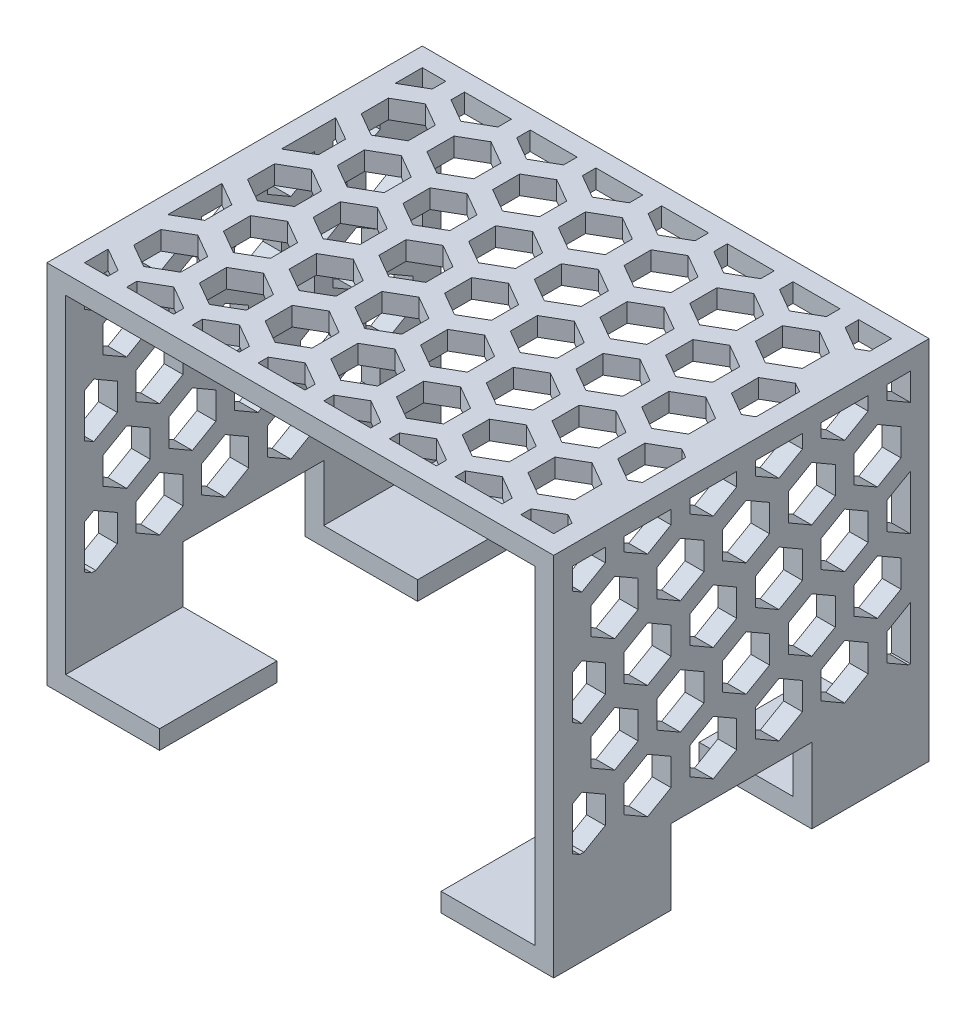
SolidWorks part; units mm, degrees
ref_plane "前视基准面" through (0, 0, 0) normal (0, 0, 1) x (1, 0, 0)
ref_plane "上视基准面" through (0, 0, 0) normal (0, 1, 0) x (1, 0, 0)
ref_plane "右视基准面" through (0, 0, 0) normal (1, 0, 0) x (0, 0, -1)
sketch "草图1" plane through (0, 0, 0) normal (0, 0, 1) x (1, 0, 0)
  line L0 (-13.2124, -10.506) -> (-23.2124, -10.506)
  line L1 (-23.2124, 24.494) -> (26.7876, 24.494)
  line L2 (-23.2124, 24.494) -> (-23.2124, -10.506)
  line L3 (-23.2124, -12.506) -> (-13.2124, -12.506)
  line L4 (26.7876, 24.494) -> (26.7876, -10.506)
  line L6 (-13.2124, -12.506) -> (-13.2124, -10.506)
  line L8 (16.7876, -12.506) -> (16.7876, -10.506)
  line L10 (-23.2124, 24.494) -> (-23.2124, -10.506)
  line L11 (-23.2124, -12.506) -> (-25.2124, -12.506)
  line L12 (-25.2124, 22.494) -> (-25.2124, -12.506)
  line L14 (26.7876, 24.494) -> (26.7876, -10.506)
  line L15 (26.7876, -12.506) -> (28.7876, -12.506)
  line L16 (28.7876, 23.4681) -> (28.7876, -12.506)
  line L17 (-23.2124, 24.494) -> (26.7876, 24.494)
  line L18 (-25.2124, 22.494) -> (-25.2124, 26.494)
  line L19 (-25.2124, 26.494) -> (28.7876, 26.494)
  line L20 (28.7876, 23.4681) -> (28.7876, 26.494)
  line L21 (16.7876, -10.506) -> (26.7876, -10.506)
  line L22 (16.7876, -12.506) -> (26.7876, -12.506)
  dimension "D1" = 50
  dimension "D2" = 37
  dimension "D3" = 30
  dimension "D4" = 10
  dimension "D5" = 2
  dimension "D6" = 2
  dimension "D7" = 2
  dimension "D9" = 2
extrude "凸台-拉伸1" add sketch "草图1" along normal blind 40 contours L8 L22 L15 L16 L20 L19 L18 L12 L11 L3 L6 L0 L2 L1 L4 L21
sketch "草图2" plane through (0, 26.494, 0) normal (0, 1, 0) x (1, 0, 0)
  line L0 (-19.7124, -10.9489) -> (-17.2124, -9.5056)
  line L1 (-23.2124, -4.8868) -> (-20.7124, -3.4434)
  line L2 (-20.7124, -3.4434) -> (-20.7124, -2)
  line L7 (-17.2124, -9.5056) -> (-17.2124, -6.6188)
  line L8 (-17.2124, -6.6188) -> (-19.7124, -5.1754)
  line L9 (-19.7124, -5.1754) -> (-22.2124, -6.6188)
  line L10 (-22.2124, -6.6188) -> (-22.2124, -9.5056)
  line L11 (-22.2124, -9.5056) -> (-19.7124, -10.9489)
  line L12 (-25.2124, 0) -> (28.7876, 0) construction
  line L13 (-16.2124, -4.8868) -> (-13.7124, -3.4434)
  line L14 (-25.2124, -40) -> (-25.2124, 0) construction
  line L15 (-13.7124, -3.4434) -> (-13.7124, -2)
  line L18 (-18.7124, -2) -> (-18.7124, -3.4434)
  line L19 (-18.7124, -3.4434) -> (-16.2124, -4.8868)
  line L20 (-12.7124, -10.9489) -> (-10.2124, -9.5056)
  line L21 (-10.2124, -9.5056) -> (-10.2124, -6.6188)
  line L22 (-10.2124, -6.6188) -> (-12.7124, -5.1754)
  line L23 (-12.7124, -5.1754) -> (-15.2124, -6.6188)
  line L24 (-15.2124, -6.6188) -> (-15.2124, -9.5056)
  line L25 (-15.2124, -9.5056) -> (-12.7124, -10.9489)
  line L26 (-9.2124, -4.8868) -> (-6.7124, -3.4434)
  line L27 (-6.7124, -3.4434) -> (-6.7124, -2)
  line L30 (-11.7124, -2) -> (-11.7124, -3.4434)
  line L31 (-11.7124, -3.4434) -> (-9.2124, -4.8868)
  line L32 (-5.7124, -10.9489) -> (-3.2124, -9.5056)
  line L33 (-3.2124, -9.5056) -> (-3.2124, -6.6188)
  line L34 (-3.2124, -6.6188) -> (-5.7124, -5.1754)
  line L35 (-5.7124, -5.1754) -> (-8.2124, -6.6188)
  line L36 (-8.2124, -6.6188) -> (-8.2124, -9.5056)
  line L37 (-8.2124, -9.5056) -> (-5.7124, -10.9489)
  line L38 (-2.2124, -4.8868) -> (0.2876, -3.4434)
  line L39 (0.2876, -3.4434) -> (0.2876, -2)
  line L42 (-4.7124, -2) -> (-4.7124, -3.4434)
  line L43 (-4.7124, -3.4434) -> (-2.2124, -4.8868)
  line L44 (1.2876, -10.9489) -> (3.7876, -9.5056)
  line L45 (3.7876, -9.5056) -> (3.7876, -6.6188)
  line L46 (3.7876, -6.6188) -> (1.2876, -5.1754)
  line L47 (1.2876, -5.1754) -> (-1.2124, -6.6188)
  line L48 (-1.2124, -6.6188) -> (-1.2124, -9.5056)
  line L49 (-1.2124, -9.5056) -> (1.2876, -10.9489)
  line L50 (4.7876, -4.8868) -> (7.2876, -3.4434)
  line L51 (7.2876, -3.4434) -> (7.2876, -2)
  line L54 (2.2876, -2) -> (2.2876, -3.4434)
  line L55 (2.2876, -3.4434) -> (4.7876, -4.8868)
  line L56 (8.2876, -10.9489) -> (10.7876, -9.5056)
  line L57 (10.7876, -9.5056) -> (10.7876, -6.6188)
  line L58 (10.7876, -6.6188) -> (8.2876, -5.1754)
  line L59 (8.2876, -5.1754) -> (5.7876, -6.6188)
  line L60 (5.7876, -6.6188) -> (5.7876, -9.5056)
  line L61 (5.7876, -9.5056) -> (8.2876, -10.9489)
  line L62 (11.7876, -4.8868) -> (14.2876, -3.4434)
  line L63 (14.2876, -3.4434) -> (14.2876, -2)
  line L66 (9.2876, -2) -> (9.2876, -3.4434)
  line L67 (9.2876, -3.4434) -> (11.7876, -4.8868)
  line L68 (15.2876, -10.9489) -> (17.7876, -9.5056)
  line L69 (17.7876, -9.5056) -> (17.7876, -6.6188)
  line L70 (17.7876, -6.6188) -> (15.2876, -5.1754)
  line L71 (15.2876, -5.1754) -> (12.7876, -6.6188)
  line L72 (12.7876, -6.6188) -> (12.7876, -9.5056)
  line L73 (12.7876, -9.5056) -> (15.2876, -10.9489)
  line L74 (18.7876, -4.8868) -> (21.2876, -3.4434)
  line L75 (21.2876, -3.4434) -> (21.2876, -2)
  line L78 (16.2876, -2) -> (16.2876, -3.4434)
  line L79 (16.2876, -3.4434) -> (18.7876, -4.8868)
  line L80 (22.2876, -10.9489) -> (24.7876, -9.5056)
  line L81 (24.7876, -9.5056) -> (24.7876, -6.6188)
  line L82 (24.7876, -6.6188) -> (22.2876, -5.1754)
  line L83 (22.2876, -5.1754) -> (19.7876, -6.6188)
  line L84 (19.7876, -6.6188) -> (19.7876, -9.5056)
  line L85 (19.7876, -9.5056) -> (22.2876, -10.9489)
  line L86 (25.7876, -4.8868) -> (26.7876, -4.3094)
  line L90 (23.2876, -2) -> (23.2876, -3.4434)
  line L91 (23.2876, -3.4434) -> (25.7876, -4.8868)
  line L98 (-16.2124, -17.0068) -> (-13.7124, -15.5634)
  line L99 (-13.7124, -15.5634) -> (-13.7124, -12.6766)
  line L100 (-13.7124, -12.6766) -> (-16.2124, -11.2332)
  line L101 (-16.2124, -11.2332) -> (-18.7124, -12.6766)
  line L102 (-18.7124, -12.6766) -> (-18.7124, -15.5634)
  line L103 (-18.7124, -15.5634) -> (-16.2124, -17.0068)
  line L104 (-12.7124, -23.0689) -> (-10.2124, -21.6256)
  line L105 (-10.2124, -21.6256) -> (-10.2124, -18.7388)
  line L106 (-10.2124, -18.7388) -> (-12.7124, -17.2954)
  line L107 (-12.7124, -17.2954) -> (-15.2124, -18.7388)
  line L108 (-15.2124, -18.7388) -> (-15.2124, -21.6256)
  line L109 (-15.2124, -21.6256) -> (-12.7124, -23.0689)
  line L110 (-9.2124, -17.0068) -> (-6.7124, -15.5634)
  line L111 (-6.7124, -15.5634) -> (-6.7124, -12.6766)
  line L112 (-6.7124, -12.6766) -> (-9.2124, -11.2332)
  line L113 (-9.2124, -11.2332) -> (-11.7124, -12.6766)
  line L114 (-11.7124, -12.6766) -> (-11.7124, -15.5634)
  line L115 (-11.7124, -15.5634) -> (-9.2124, -17.0068)
  line L116 (-5.7124, -23.0689) -> (-3.2124, -21.6256)
  line L117 (-3.2124, -21.6256) -> (-3.2124, -18.7388)
  line L118 (-3.2124, -18.7388) -> (-5.7124, -17.2954)
  line L119 (-5.7124, -17.2954) -> (-8.2124, -18.7388)
  line L120 (-8.2124, -18.7388) -> (-8.2124, -21.6256)
  line L121 (-8.2124, -21.6256) -> (-5.7124, -23.0689)
  line L122 (-2.2124, -17.0068) -> (0.2876, -15.5634)
  line L123 (0.2876, -15.5634) -> (0.2876, -12.6766)
  line L124 (0.2876, -12.6766) -> (-2.2124, -11.2332)
  line L125 (-2.2124, -11.2332) -> (-4.7124, -12.6766)
  line L126 (-4.7124, -12.6766) -> (-4.7124, -15.5634)
  line L127 (-4.7124, -15.5634) -> (-2.2124, -17.0068)
  line L128 (1.2876, -23.0689) -> (3.7876, -21.6256)
  line L129 (3.7876, -21.6256) -> (3.7876, -18.7388)
  line L130 (3.7876, -18.7388) -> (1.2876, -17.2954)
  line L131 (1.2876, -17.2954) -> (-1.2124, -18.7388)
  line L132 (-1.2124, -18.7388) -> (-1.2124, -21.6256)
  line L133 (-1.2124, -21.6256) -> (1.2876, -23.0689)
  line L134 (4.7876, -17.0068) -> (7.2876, -15.5634)
  line L135 (7.2876, -15.5634) -> (7.2876, -12.6766)
  line L136 (7.2876, -12.6766) -> (4.7876, -11.2332)
  line L137 (4.7876, -11.2332) -> (2.2876, -12.6766)
  line L138 (2.2876, -12.6766) -> (2.2876, -15.5634)
  line L139 (2.2876, -15.5634) -> (4.7876, -17.0068)
  line L140 (8.2876, -23.0689) -> (10.7876, -21.6256)
  line L141 (10.7876, -21.6256) -> (10.7876, -18.7388)
  line L142 (10.7876, -18.7388) -> (8.2876, -17.2954)
  line L143 (8.2876, -17.2954) -> (5.7876, -18.7388)
  line L144 (5.7876, -18.7388) -> (5.7876, -21.6256)
  line L145 (5.7876, -21.6256) -> (8.2876, -23.0689)
  line L146 (11.7876, -17.0068) -> (14.2876, -15.5634)
  line L147 (14.2876, -15.5634) -> (14.2876, -12.6766)
  line L148 (14.2876, -12.6766) -> (11.7876, -11.2332)
  line L149 (11.7876, -11.2332) -> (9.2876, -12.6766)
  line L150 (9.2876, -12.6766) -> (9.2876, -15.5634)
  line L151 (9.2876, -15.5634) -> (11.7876, -17.0068)
  line L152 (15.2876, -23.0689) -> (17.7876, -21.6256)
  line L153 (17.7876, -21.6256) -> (17.7876, -18.7388)
  line L154 (17.7876, -18.7388) -> (15.2876, -17.2954)
  line L155 (15.2876, -17.2954) -> (12.7876, -18.7388)
  line L156 (12.7876, -18.7388) -> (12.7876, -21.6256)
  line L157 (12.7876, -21.6256) -> (15.2876, -23.0689)
  line L158 (18.7876, -17.0068) -> (21.2876, -15.5634)
  line L159 (21.2876, -15.5634) -> (21.2876, -12.6766)
  line L160 (21.2876, -12.6766) -> (18.7876, -11.2332)
  line L161 (18.7876, -11.2332) -> (16.2876, -12.6766)
  line L162 (16.2876, -12.6766) -> (16.2876, -15.5634)
  line L163 (16.2876, -15.5634) -> (18.7876, -17.0068)
  line L164 (22.2876, -23.0689) -> (24.7876, -21.6256)
  line L165 (24.7876, -21.6256) -> (24.7876, -18.7388)
  line L166 (24.7876, -18.7388) -> (22.2876, -17.2954)
  line L167 (22.2876, -17.2954) -> (19.7876, -18.7388)
  line L168 (19.7876, -18.7388) -> (19.7876, -21.6256)
  line L169 (19.7876, -21.6256) -> (22.2876, -23.0689)
  line L170 (25.7876, -17.0068) -> (26.7876, -16.4294)
  line L172 (26.7876, -11.8106) -> (25.7876, -11.2332)
  line L173 (25.7876, -11.2332) -> (23.2876, -12.6766)
  line L174 (23.2876, -12.6766) -> (23.2876, -15.5634)
  line L175 (23.2876, -15.5634) -> (25.7876, -17.0068)
  line L182 (-16.2124, -29.1268) -> (-13.7124, -27.6834)
  line L183 (-13.7124, -27.6834) -> (-13.7124, -24.7966)
  line L184 (-13.7124, -24.7966) -> (-16.2124, -23.3532)
  line L185 (-16.2124, -23.3532) -> (-18.7124, -24.7966)
  line L186 (-18.7124, -24.7966) -> (-18.7124, -27.6834)
  line L187 (-18.7124, -27.6834) -> (-16.2124, -29.1268)
  line L188 (-12.7124, -35.1889) -> (-10.2124, -33.7456)
  line L189 (-10.2124, -33.7456) -> (-10.2124, -30.8588)
  line L190 (-10.2124, -30.8588) -> (-12.7124, -29.4154)
  line L191 (-12.7124, -29.4154) -> (-15.2124, -30.8588)
  line L192 (-15.2124, -30.8588) -> (-15.2124, -33.7456)
  line L193 (-15.2124, -33.7456) -> (-12.7124, -35.1889)
  line L194 (-9.2124, -29.1268) -> (-6.7124, -27.6834)
  line L195 (-6.7124, -27.6834) -> (-6.7124, -24.7966)
  line L196 (-6.7124, -24.7966) -> (-9.2124, -23.3532)
  line L197 (-9.2124, -23.3532) -> (-11.7124, -24.7966)
  line L198 (-11.7124, -24.7966) -> (-11.7124, -27.6834)
  line L199 (-11.7124, -27.6834) -> (-9.2124, -29.1268)
  line L200 (-5.7124, -35.1889) -> (-3.2124, -33.7456)
  line L201 (-3.2124, -33.7456) -> (-3.2124, -30.8588)
  line L202 (-3.2124, -30.8588) -> (-5.7124, -29.4154)
  line L203 (-5.7124, -29.4154) -> (-8.2124, -30.8588)
  line L204 (-8.2124, -30.8588) -> (-8.2124, -33.7456)
  line L205 (-8.2124, -33.7456) -> (-5.7124, -35.1889)
  line L206 (-2.2124, -29.1268) -> (0.2876, -27.6834)
  line L207 (0.2876, -27.6834) -> (0.2876, -24.7966)
  line L208 (0.2876, -24.7966) -> (-2.2124, -23.3532)
  line L209 (-2.2124, -23.3532) -> (-4.7124, -24.7966)
  line L210 (-4.7124, -24.7966) -> (-4.7124, -27.6834)
  line L211 (-4.7124, -27.6834) -> (-2.2124, -29.1268)
  line L212 (1.2876, -35.1889) -> (3.7876, -33.7456)
  line L213 (3.7876, -33.7456) -> (3.7876, -30.8588)
  line L214 (3.7876, -30.8588) -> (1.2876, -29.4154)
  line L215 (1.2876, -29.4154) -> (-1.2124, -30.8588)
  line L216 (-1.2124, -30.8588) -> (-1.2124, -33.7456)
  line L217 (-1.2124, -33.7456) -> (1.2876, -35.1889)
  line L218 (4.7876, -29.1268) -> (7.2876, -27.6834)
  line L219 (7.2876, -27.6834) -> (7.2876, -24.7966)
  line L220 (7.2876, -24.7966) -> (4.7876, -23.3532)
  line L221 (4.7876, -23.3532) -> (2.2876, -24.7966)
  line L222 (2.2876, -24.7966) -> (2.2876, -27.6834)
  line L223 (2.2876, -27.6834) -> (4.7876, -29.1268)
  line L224 (8.2876, -35.1889) -> (10.7876, -33.7456)
  line L225 (10.7876, -33.7456) -> (10.7876, -30.8588)
  line L226 (10.7876, -30.8588) -> (8.2876, -29.4154)
  line L227 (8.2876, -29.4154) -> (5.7876, -30.8588)
  line L228 (5.7876, -30.8588) -> (5.7876, -33.7456)
  line L229 (5.7876, -33.7456) -> (8.2876, -35.1889)
  line L230 (11.7876, -29.1268) -> (14.2876, -27.6834)
  line L231 (14.2876, -27.6834) -> (14.2876, -24.7966)
  line L232 (14.2876, -24.7966) -> (11.7876, -23.3532)
  line L233 (11.7876, -23.3532) -> (9.2876, -24.7966)
  line L234 (9.2876, -24.7966) -> (9.2876, -27.6834)
  line L235 (9.2876, -27.6834) -> (11.7876, -29.1268)
  line L236 (15.2876, -35.1889) -> (17.7876, -33.7456)
  line L237 (17.7876, -33.7456) -> (17.7876, -30.8588)
  line L238 (17.7876, -30.8588) -> (15.2876, -29.4154)
  line L239 (15.2876, -29.4154) -> (12.7876, -30.8588)
  line L240 (12.7876, -30.8588) -> (12.7876, -33.7456)
  line L241 (12.7876, -33.7456) -> (15.2876, -35.1889)
  line L242 (18.7876, -29.1268) -> (21.2876, -27.6834)
  line L243 (21.2876, -27.6834) -> (21.2876, -24.7966)
  line L244 (21.2876, -24.7966) -> (18.7876, -23.3532)
  line L245 (18.7876, -23.3532) -> (16.2876, -24.7966)
  line L246 (16.2876, -24.7966) -> (16.2876, -27.6834)
  line L247 (16.2876, -27.6834) -> (18.7876, -29.1268)
  line L248 (22.2876, -35.1889) -> (24.7876, -33.7456)
  line L249 (24.7876, -33.7456) -> (24.7876, -30.8588)
  line L250 (24.7876, -30.8588) -> (22.2876, -29.4154)
  line L251 (22.2876, -29.4154) -> (19.7876, -30.8588)
  line L252 (19.7876, -30.8588) -> (19.7876, -33.7456)
  line L253 (19.7876, -33.7456) -> (22.2876, -35.1889)
  line L254 (25.7876, -29.1268) -> (26.7876, -28.5494)
  line L256 (26.7876, -23.9306) -> (25.7876, -23.3532)
  line L257 (25.7876, -23.3532) -> (23.2876, -24.7966)
  line L258 (23.2876, -24.7966) -> (23.2876, -27.6834)
  line L259 (23.2876, -27.6834) -> (25.7876, -29.1268)
  line L267 (-13.7124, -38) -> (-13.7124, -36.9166)
  line L268 (-13.7124, -36.9166) -> (-16.2124, -35.4732)
  line L269 (-16.2124, -35.4732) -> (-18.7124, -36.9166)
  line L270 (-18.7124, -36.9166) -> (-18.7124, -38)
  line L279 (-6.7124, -38) -> (-6.7124, -36.9166)
  line L280 (-6.7124, -36.9166) -> (-9.2124, -35.4732)
  line L281 (-9.2124, -35.4732) -> (-11.7124, -36.9166)
  line L282 (-11.7124, -36.9166) -> (-11.7124, -38)
  line L291 (0.2876, -38) -> (0.2876, -36.9166)
  line L292 (0.2876, -36.9166) -> (-2.2124, -35.4732)
  line L293 (-2.2124, -35.4732) -> (-4.7124, -36.9166)
  line L294 (-4.7124, -36.9166) -> (-4.7124, -38)
  line L303 (7.2876, -38) -> (7.2876, -36.9166)
  line L304 (7.2876, -36.9166) -> (4.7876, -35.4732)
  line L305 (4.7876, -35.4732) -> (2.2876, -36.9166)
  line L306 (2.2876, -36.9166) -> (2.2876, -38)
  line L315 (14.2876, -38) -> (14.2876, -36.9166)
  line L316 (14.2876, -36.9166) -> (11.7876, -35.4732)
  line L317 (11.7876, -35.4732) -> (9.2876, -36.9166)
  line L318 (9.2876, -36.9166) -> (9.2876, -38)
  line L327 (21.2876, -38) -> (21.2876, -36.9166)
  line L328 (21.2876, -36.9166) -> (18.7876, -35.4732)
  line L329 (18.7876, -35.4732) -> (16.2876, -36.9166)
  line L330 (16.2876, -36.9166) -> (16.2876, -38)
  line L340 (26.7876, -36.0506) -> (25.7876, -35.4732)
  line L341 (25.7876, -35.4732) -> (23.2876, -36.9166)
  line L342 (23.2876, -36.9166) -> (23.2876, -38)
  line L350 (-23.2124, -17.0068) -> (-20.7124, -15.5634)
  line L351 (-20.7124, -15.5634) -> (-20.7124, -12.6766)
  line L352 (-20.7124, -12.6766) -> (-23.2124, -11.2332)
  line L356 (-19.7124, -23.0689) -> (-17.2124, -21.6256)
  line L357 (-17.2124, -21.6256) -> (-17.2124, -18.7388)
  line L358 (-17.2124, -18.7388) -> (-19.7124, -17.2954)
  line L359 (-19.7124, -17.2954) -> (-22.2124, -18.7388)
  line L360 (-22.2124, -18.7388) -> (-22.2124, -21.6256)
  line L361 (-22.2124, -21.6256) -> (-19.7124, -23.0689)
  line L362 (-23.2124, -29.1268) -> (-20.7124, -27.6834)
  line L363 (-20.7124, -27.6834) -> (-20.7124, -24.7966)
  line L364 (-20.7124, -24.7966) -> (-23.2124, -23.3532)
  line L368 (-19.7124, -35.1889) -> (-17.2124, -33.7456)
  line L369 (-17.2124, -33.7456) -> (-17.2124, -30.8588)
  line L370 (-17.2124, -30.8588) -> (-19.7124, -29.4154)
  line L371 (-19.7124, -29.4154) -> (-22.2124, -30.8588)
  line L372 (-22.2124, -30.8588) -> (-22.2124, -33.7456)
  line L373 (-22.2124, -33.7456) -> (-19.7124, -35.1889)
  line L375 (-20.7124, -38) -> (-20.7124, -36.9166)
  line L376 (-20.7124, -36.9166) -> (-23.2124, -35.4732)
  line L386 (-25.2124, -40) -> (28.7876, -40) construction
  line L387 (-23.2124, -2) -> (-20.7124, -2)
  line L388 (-23.2124, -2) -> (-23.2124, -4.8868)
  line L389 (-23.2124, -38) -> (-20.7124, -38)
  line L390 (26.7876, -2) -> (26.7876, -4.3094)
  line L393 (26.7876, 0) -> (26.7876, -40) construction
  line L395 (26.7876, -11.8106) -> (26.7876, -16.4294)
  line L396 (-23.2124, 0.8868) -> (-25.7124, -0.5566) [skipped]
  line L397 (-25.7124, -0.5566) -> (-25.7124, -3.4434) [skipped]
  line L398 (-25.7124, -3.4434) -> (-23.2124, -4.8868) [skipped]
  line L399 (28.2876, -3.4434) -> (28.2876, -0.5566) [skipped]
  line L401 (29.2876, -10.9489) -> (31.7876, -9.5056) [skipped]
  line L402 (31.7876, -9.5056) -> (31.7876, -6.6188) [skipped]
  line L403 (31.7876, -6.6188) -> (29.2876, -5.1754) [skipped]
  line L404 (29.2876, -5.1754) -> (26.7876, -6.6188) [skipped]
  line L405 (26.7876, -9.5056) -> (29.2876, -10.9489) [skipped]
  line L406 (28.2876, -15.5634) -> (28.2876, -12.6766) [skipped]
  line L407 (29.2876, -23.0689) -> (31.7876, -21.6256) [skipped]
  line L408 (31.7876, -21.6256) -> (31.7876, -18.7388) [skipped]
  line L409 (31.7876, -18.7388) -> (29.2876, -17.2954) [skipped]
  line L410 (29.2876, -17.2954) -> (26.7876, -18.7388) [skipped]
  line L411 (26.7876, -21.6256) -> (29.2876, -23.0689) [skipped]
  line L412 (28.2876, -27.6834) -> (28.2876, -24.7966) [skipped]
  line L413 (29.2876, -35.1889) -> (31.7876, -33.7456) [skipped]
  line L414 (31.7876, -33.7456) -> (31.7876, -30.8588) [skipped]
  line L415 (31.7876, -30.8588) -> (29.2876, -29.4154) [skipped]
  line L416 (29.2876, -29.4154) -> (26.7876, -30.8588) [skipped]
  line L417 (26.7876, -33.7456) -> (29.2876, -35.1889) [skipped]
  line L418 (-12.7124, -47.3089) -> (-10.2124, -45.8656) [skipped]
  line L419 (-10.2124, -45.8656) -> (-10.2124, -42.9788) [skipped]
  line L420 (-10.2124, -42.9788) -> (-12.7124, -41.5354) [skipped]
  line L421 (-12.7124, -41.5354) -> (-15.2124, -42.9788) [skipped]
  line L422 (-15.2124, -42.9788) -> (-15.2124, -45.8656) [skipped]
  line L423 (-15.2124, -45.8656) -> (-12.7124, -47.3089) [skipped]
  line L424 (-5.7124, -47.3089) -> (-3.2124, -45.8656) [skipped]
  line L425 (-3.2124, -45.8656) -> (-3.2124, -42.9788) [skipped]
  line L426 (-3.2124, -42.9788) -> (-5.7124, -41.5354) [skipped]
  line L427 (-5.7124, -41.5354) -> (-8.2124, -42.9788) [skipped]
  line L428 (-8.2124, -42.9788) -> (-8.2124, -45.8656) [skipped]
  line L429 (-8.2124, -45.8656) -> (-5.7124, -47.3089) [skipped]
  line L430 (1.2876, -47.3089) -> (3.7876, -45.8656) [skipped]
  line L431 (3.7876, -45.8656) -> (3.7876, -42.9788) [skipped]
  line L432 (3.7876, -42.9788) -> (1.2876, -41.5354) [skipped]
  line L433 (1.2876, -41.5354) -> (-1.2124, -42.9788) [skipped]
  line L434 (-1.2124, -42.9788) -> (-1.2124, -45.8656) [skipped]
  line L435 (-1.2124, -45.8656) -> (1.2876, -47.3089) [skipped]
  line L436 (8.2876, -47.3089) -> (10.7876, -45.8656) [skipped]
  line L437 (10.7876, -45.8656) -> (10.7876, -42.9788) [skipped]
  line L438 (10.7876, -42.9788) -> (8.2876, -41.5354) [skipped]
  line L439 (8.2876, -41.5354) -> (5.7876, -42.9788) [skipped]
  line L440 (5.7876, -42.9788) -> (5.7876, -45.8656) [skipped]
  line L441 (5.7876, -45.8656) -> (8.2876, -47.3089) [skipped]
  line L442 (15.2876, -47.3089) -> (17.7876, -45.8656) [skipped]
  line L443 (17.7876, -45.8656) -> (17.7876, -42.9788) [skipped]
  line L444 (17.7876, -42.9788) -> (15.2876, -41.5354) [skipped]
  line L445 (15.2876, -41.5354) -> (12.7876, -42.9788) [skipped]
  line L446 (12.7876, -42.9788) -> (12.7876, -45.8656) [skipped]
  line L447 (12.7876, -45.8656) -> (15.2876, -47.3089) [skipped]
  line L448 (22.2876, -47.3089) -> (24.7876, -45.8656) [skipped]
  line L449 (24.7876, -45.8656) -> (24.7876, -42.9788) [skipped]
  line L450 (24.7876, -42.9788) -> (22.2876, -41.5354) [skipped]
  line L451 (22.2876, -41.5354) -> (19.7876, -42.9788) [skipped]
  line L452 (19.7876, -42.9788) -> (19.7876, -45.8656) [skipped]
  line L453 (19.7876, -45.8656) -> (22.2876, -47.3089) [skipped]
  line L454 (25.7876, -41.2468) -> (28.2876, -39.8034) [skipped]
  line L455 (28.2876, -39.8034) -> (28.2876, -36.9166) [skipped]
  line L456 (29.2876, -47.3089) -> (31.7876, -45.8656) [skipped]
  line L457 (31.7876, -45.8656) -> (31.7876, -42.9788) [skipped]
  line L458 (31.7876, -42.9788) -> (29.2876, -41.5354) [skipped]
  line L459 (29.2876, -41.5354) -> (26.7876, -42.9788) [skipped]
  line L460 (26.7876, -42.9788) -> (26.7876, -45.8656) [skipped]
  line L461 (26.7876, -45.8656) -> (29.2876, -47.3089) [skipped]
  line L462 (-19.7124, -47.3089) -> (-17.2124, -45.8656) [skipped]
  line L463 (-17.2124, -45.8656) -> (-17.2124, -42.9788) [skipped]
  line L464 (-17.2124, -42.9788) -> (-19.7124, -41.5354) [skipped]
  line L465 (-19.7124, -41.5354) -> (-22.2124, -42.9788) [skipped]
  line L466 (-22.2124, -42.9788) -> (-22.2124, -45.8656) [skipped]
  line L467 (-22.2124, -45.8656) -> (-19.7124, -47.3089) [skipped]
  line L468 (2.2876, -2) -> (7.2876, -2)
  line L469 (6.947, -40) -> (7.2876, -39.8034) [skipped]
  line L470 (-21.053, -40) -> (-20.7124, -39.8034) [skipped]
  line L471 (20.947, -40) -> (21.2876, -39.8034) [skipped]
  line L472 (13.947, -40) -> (14.2876, -39.8034) [skipped]
  line L473 (26.7876, -6.6188) -> (26.7876, -9.5056) [skipped]
  line L474 (23.2876, -2) -> (26.7876, -2)
  line L475 (16.2876, -2) -> (21.2876, -2)
  line L476 (9.2876, -2) -> (14.2876, -2)
  line L477 (26.7876, -36.0506) -> (26.7876, -38)
  line L478 (26.7876, -30.8588) -> (26.7876, -33.7456) [skipped]
  line L479 (26.7876, -23.9306) -> (26.7876, -28.5494)
  line L480 (26.7876, -18.7388) -> (26.7876, -21.6256) [skipped]
  line L481 (-4.7124, -2) -> (0.2876, -2)
  line L482 (-11.7124, -2) -> (-6.7124, -2)
  line L483 (-23.2124, -23.3532) -> (-23.2124, -29.1268)
  line L484 (-23.2124, -35.4732) -> (-23.2124, -38)
  line L485 (-18.7124, -38) -> (-13.7124, -38)
  line L486 (-11.7124, -38) -> (-6.7124, -38)
  line L487 (-4.7124, -38) -> (0.2876, -38)
  line L488 (2.2876, -38) -> (7.2876, -38)
  line L489 (9.2876, -38) -> (14.2876, -38)
  line L490 (16.2876, -38) -> (21.2876, -38)
  line L491 (23.2876, -38) -> (26.7876, -38)
  line L492 (-0.053, -40) -> (0.2876, -39.8034) [skipped]
  line L493 (-23.2124, -11.2332) -> (-23.2124, -17.0068)
  line L494 (-20.7124, -0.5566) -> (-21.6765, 0) [skipped]
  line L495 (-18.7124, -2) -> (-13.7124, -2)
  line L496 (-14.053, -40) -> (-13.7124, -39.8034) [skipped]
  line L497 (-7.053, -40) -> (-6.7124, -39.8034) [skipped]
  arc A0 (-23.2124, -4.5) -> (-20.7124, -2) centre (-23.2124, -2) ccw construction
  circle A1 centre (-19.7124, -8.0622) radius 2.5 construction
  point P104 (-21.9492, -63.3958)
  dimension "D1" = 2
  dimension "D2" = 2
  dimension "D3" = 2
  dimension "D4" = 2
  dimension "D5" = 2
  dimension "D8" = 2
  dimension "D9" = 2
  dimension "D10" = 2
  dimension "D6" = 8
  dimension "D7" = 4
extrude "切除-拉伸1" cut sketch "草图2" against normal up to next (2 mm away)
sketch "草图3" plane through (-25.2124, 0, 0) normal (-1, 0, 0) x (0, 0, 1)
  line L0 (40, -12.506) -> (0, -12.506) construction
  line L1 (12.5, -12.506) -> (27.5, -12.506)
  line L2 (12.5, -12.506) -> (12.5, -4.506)
  line L3 (12.5, -4.506) -> (27.5, -4.506)
  line L4 (27.5, -12.506) -> (27.5, -4.506)
  line L5 (0, -12.506) -> (0, 26.494) construction
  dimension "D1" = 8
  dimension "D2" = 15
  dimension "D3" = 12.5
extrude "切除-拉伸2" cut sketch "草图3" against normal blind 74
sketch "草图4" plane through (-25.2124, 0, 0) normal (-1, 0, 0) x (0, 0, 1)
  line L4 (2, 21.6072) -> (4.5, 23.0506)
  line L5 (4.5, 23.0506) -> (4.5, 24.494)
  line L7 (5.5, 21.3185) -> (3, 19.8752)
  line L8 (3, 19.8752) -> (3, 16.9884)
  line L9 (3, 16.9884) -> (5.5, 15.545)
  line L10 (5.5, 15.545) -> (8, 16.9884)
  line L11 (8, 16.9884) -> (8, 19.8752)
  line L12 (8, 19.8752) -> (5.5, 21.3185)
  line L13 (6.5, 24.494) -> (6.5, 23.0506)
  line L14 (6.5, 23.0506) -> (9, 21.6072)
  line L15 (9, 21.6072) -> (11.5, 23.0506)
  line L16 (11.5, 23.0506) -> (11.5, 24.494)
  line L18 (12.5, 21.3185) -> (10, 19.8752)
  line L19 (10, 19.8752) -> (10, 16.9884)
  line L20 (10, 16.9884) -> (12.5, 15.545)
  line L21 (12.5, 15.545) -> (15, 16.9884)
  line L22 (15, 16.9884) -> (15, 19.8752)
  line L23 (15, 19.8752) -> (12.5, 21.3185)
  line L25 (13.5, 24.494) -> (13.5, 23.0506)
  line L26 (13.5, 23.0506) -> (16, 21.6072)
  line L27 (16, 21.6072) -> (18.5, 23.0506)
  line L28 (18.5, 23.0506) -> (18.5, 24.494)
  line L30 (19.5, 21.3185) -> (17, 19.8752)
  line L31 (17, 19.8752) -> (17, 16.9884)
  line L32 (17, 16.9884) -> (19.5, 15.545)
  line L33 (19.5, 15.545) -> (22, 16.9884)
  line L34 (22, 16.9884) -> (22, 19.8752)
  line L35 (22, 19.8752) -> (19.5, 21.3185)
  line L37 (20.5, 24.494) -> (20.5, 23.0506)
  line L38 (20.5, 23.0506) -> (23, 21.6072)
  line L39 (23, 21.6072) -> (25.5, 23.0506)
  line L40 (25.5, 23.0506) -> (25.5, 24.494)
  line L42 (26.5, 21.3185) -> (24, 19.8752)
  line L43 (24, 19.8752) -> (24, 16.9884)
  line L44 (24, 16.9884) -> (26.5, 15.545)
  line L45 (26.5, 15.545) -> (29, 16.9884)
  line L46 (29, 16.9884) -> (29, 19.8752)
  line L47 (29, 19.8752) -> (26.5, 21.3185)
  line L49 (27.5, 24.494) -> (27.5, 23.0506)
  line L50 (27.5, 23.0506) -> (30, 21.6072)
  line L51 (30, 21.6072) -> (32.5, 23.0506)
  line L52 (32.5, 23.0506) -> (32.5, 24.494)
  line L54 (33.5, 21.3185) -> (31, 19.8752)
  line L55 (31, 19.8752) -> (31, 16.9884)
  line L56 (31, 16.9884) -> (33.5, 15.545)
  line L57 (33.5, 15.545) -> (36, 16.9884)
  line L58 (36, 16.9884) -> (36, 19.8752)
  line L59 (36, 19.8752) -> (33.5, 21.3185)
  line L61 (34.5, 24.494) -> (34.5, 23.0506)
  line L62 (34.5, 23.0506) -> (37, 21.6072)
  line L63 (37, 21.6072) -> (38, 22.1846)
  line L72 (9, 15.2607) -> (6.5, 13.8173)
  line L73 (6.5, 13.8173) -> (6.5, 10.9306)
  line L74 (6.5, 10.9306) -> (9, 9.4872)
  line L75 (9, 9.4872) -> (11.5, 10.9306)
  line L76 (11.5, 10.9306) -> (11.5, 13.8173)
  line L77 (11.5, 13.8173) -> (9, 15.2607)
  line L78 (12.5, 9.1985) -> (10, 7.7552)
  line L79 (10, 7.7552) -> (10, 4.8684)
  line L80 (10, 4.8684) -> (12.5, 3.425)
  line L81 (12.5, 3.425) -> (15, 4.8684)
  line L82 (15, 4.8684) -> (15, 7.7552)
  line L83 (15, 7.7552) -> (12.5, 9.1985)
  line L84 (16, 15.2607) -> (13.5, 13.8173)
  line L85 (13.5, 13.8173) -> (13.5, 10.9306)
  line L86 (13.5, 10.9306) -> (16, 9.4872)
  line L87 (16, 9.4872) -> (18.5, 10.9306)
  line L88 (18.5, 10.9306) -> (18.5, 13.8173)
  line L89 (18.5, 13.8173) -> (16, 15.2607)
  line L90 (19.5, 9.1985) -> (17, 7.7552)
  line L91 (17, 7.7552) -> (17, 4.8684)
  line L92 (17, 4.8684) -> (19.5, 3.425)
  line L93 (19.5, 3.425) -> (22, 4.8684)
  line L94 (22, 4.8684) -> (22, 7.7552)
  line L95 (22, 7.7552) -> (19.5, 9.1985)
  line L96 (23, 15.2607) -> (20.5, 13.8173)
  line L97 (20.5, 13.8173) -> (20.5, 10.9306)
  line L98 (20.5, 10.9306) -> (23, 9.4872)
  line L99 (23, 9.4872) -> (25.5, 10.9306)
  line L100 (25.5, 10.9306) -> (25.5, 13.8173)
  line L101 (25.5, 13.8173) -> (23, 15.2607)
  line L102 (26.5, 9.1985) -> (24, 7.7552)
  line L103 (24, 7.7552) -> (24, 4.8684)
  line L104 (24, 4.8684) -> (26.5, 3.425)
  line L105 (26.5, 3.425) -> (29, 4.8684)
  line L106 (29, 4.8684) -> (29, 7.7552)
  line L107 (29, 7.7552) -> (26.5, 9.1985)
  line L108 (30, 15.2607) -> (27.5, 13.8173)
  line L109 (27.5, 13.8173) -> (27.5, 10.9306)
  line L110 (27.5, 10.9306) -> (30, 9.4872)
  line L111 (30, 9.4872) -> (32.5, 10.9306)
  line L112 (32.5, 10.9306) -> (32.5, 13.8173)
  line L113 (32.5, 13.8173) -> (30, 15.2607)
  line L114 (33.5, 9.1985) -> (31, 7.7552)
  line L115 (31, 7.7552) -> (31, 4.8684)
  line L116 (31, 4.8684) -> (33.5, 3.425)
  line L117 (33.5, 3.425) -> (36, 4.8684)
  line L118 (36, 4.8684) -> (36, 7.7552)
  line L119 (36, 7.7552) -> (33.5, 9.1985)
  line L120 (37, 15.2607) -> (34.5, 13.8173)
  line L121 (34.5, 13.8173) -> (34.5, 10.9306)
  line L122 (34.5, 10.9306) -> (37, 9.4872)
  line L123 (37, 9.4872) -> (38, 10.0646)
  line L125 (38, 14.6834) -> (37, 15.2607)
  line L132 (9, 3.1407) -> (6.5, 1.6973)
  line L133 (6.5, 1.6973) -> (6.5, -1.1894)
  line L134 (6.5, -1.1894) -> (9, -2.6328)
  line L135 (9, -2.6328) -> (11.5, -1.1894)
  line L136 (11.5, -1.1894) -> (11.5, 1.6973)
  line L137 (11.5, 1.6973) -> (9, 3.1407)
  line L144 (16, 3.1407) -> (13.5, 1.6973)
  line L145 (13.5, 1.6973) -> (13.5, -1.1894)
  line L146 (13.5, -1.1894) -> (16, -2.6328)
  line L147 (16, -2.6328) -> (18.5, -1.1894)
  line L148 (18.5, -1.1894) -> (18.5, 1.6973)
  line L149 (18.5, 1.6973) -> (16, 3.1407)
  line L156 (23, 3.1407) -> (20.5, 1.6973)
  line L157 (20.5, 1.6973) -> (20.5, -1.1894)
  line L158 (20.5, -1.1894) -> (23, -2.6328)
  line L159 (23, -2.6328) -> (25.5, -1.1894)
  line L160 (25.5, -1.1894) -> (25.5, 1.6973)
  line L161 (25.5, 1.6973) -> (23, 3.1407)
  line L168 (30, 3.1407) -> (27.5, 1.6973)
  line L169 (27.5, 1.6973) -> (27.5, -1.1894)
  line L170 (27.5, -1.1894) -> (30, -2.6328)
  line L171 (30, -2.6328) -> (32.5, -1.1894)
  line L172 (32.5, -1.1894) -> (32.5, 1.6973)
  line L173 (32.5, 1.6973) -> (30, 3.1407)
  line L180 (37, 3.1407) -> (34.5, 1.6973)
  line L181 (34.5, 1.6973) -> (34.5, -1.1894)
  line L182 (34.5, -1.1894) -> (37, -2.6328)
  line L183 (37, -2.6328) -> (38, -2.0554)
  line L185 (38, 2.5634) -> (37, 3.1407)
  line L195 (2, 9.4872) -> (4.5, 10.9306)
  line L196 (4.5, 10.9306) -> (4.5, 13.8173)
  line L197 (4.5, 13.8173) -> (2, 15.2607)
  line L198 (5.5, 9.1985) -> (3, 7.7552)
  line L199 (3, 7.7552) -> (3, 4.8684)
  line L200 (3, 4.8684) -> (5.5, 3.425)
  line L201 (5.5, 3.425) -> (8, 4.8684)
  line L202 (8, 4.8684) -> (8, 7.7552)
  line L203 (8, 7.7552) -> (5.5, 9.1985)
  line L207 (2.2195, -2.506) -> (4.5, -1.1894)
  line L208 (4.5, -1.1894) -> (4.5, 1.6973)
  line L209 (4.5, 1.6973) -> (2, 3.1407)
  line L216 (40, 26.494) -> (0, 26.494) construction
  line L217 (0, -12.506) -> (0, 26.494) construction
  line L218 (2, 24.494) -> (4.5, 24.494)
  line L219 (2, 24.494) -> (2, 21.6072)
  line L220 (2, -2.506) -> (2.2195, -2.506)
  line L221 (38, 24.494) -> (38, 22.1846)
  line L222 (40, -12.506) -> (40, 26.494) construction
  line L223 (27.5, -4.506) -> (12.5, -4.506) construction
  line L224 (2, 15.2607) -> (2, 9.4872)
  line L225 (2, 3.1407) -> (2, -2.506)
  line L226 (38, 14.6834) -> (38, 10.0646)
  line L227 (38, 2.5634) -> (38, -2.0554)
  line L229 (6.5, 24.494) -> (11.5, 24.494)
  line L230 (0.75, 22.3289) -> (2, 21.6072) [skipped]
  line L231 (-0.5, 25.9373) -> (-0.5, 24.494) [skipped]
  line L232 (0.75, 26.659) -> (-0.5, 25.9373) [skipped]
  line L233 (4.5, 25.9373) -> (3.25, 26.659) [skipped]
  line L234 (38, -7.2516) -> (39.25, -7.9733) [skipped]
  line L235 (38, -4.3648) -> (38, -7.2516) [skipped]
  line L236 (38, 19.8752) -> (38, 16.9884) [skipped]
  line L237 (38, 7.7552) -> (38, 4.8684) [skipped]
  line L238 (39.5, 10.9306) -> (39.5, 13.8173) [skipped]
  line L239 (40.5, 9.1985) -> (39.25, 8.4769) [skipped]
  line L240 (39.5, -1.1894) -> (39.5, 1.6973) [skipped]
  line L241 (43, 7.7552) -> (41.75, 8.4769) [skipped]
  line L242 (43, 4.8684) -> (43, 7.7552) [skipped]
  line L243 (41.75, 4.1467) -> (43, 4.8684) [skipped]
  line L244 (39.25, 4.1467) -> (40.5, 3.425) [skipped]
  line L245 (39.25, 16.2667) -> (40.5, 15.545) [skipped]
  line L246 (41.75, 16.2667) -> (43, 16.9884) [skipped]
  line L247 (43, 18.4318) -> (43, 19.8752) [skipped]
  line L248 (40.5, 21.3185) -> (39.25, 20.5969) [skipped]
  line L249 (41.75, 20.5969) -> (40.5, 21.3185) [skipped]
  line L250 (41.75, -3.6431) -> (40.5, -2.9215) [skipped]
  line L251 (40.5, -2.9215) -> (39.25, -3.6431) [skipped]
  line L252 (43, -7.2516) -> (43, -4.3648) [skipped]
  line L253 (40.5, -8.695) -> (43, -7.2516) [skipped]
  line L254 (36, -5.8082) -> (36, -4.3648) [skipped]
  line L255 (31, -5.8082) -> (31, -7.2516) [skipped]
  line L256 (33.5, -2.9215) -> (32.25, -3.6431) [skipped]
  line L257 (34.75, -3.6431) -> (33.5, -2.9215) [skipped]
  line L258 (31, -7.2516) -> (33.5, -8.695) [skipped]
  line L259 (33.5, -8.695) -> (34.75, -7.9733) [skipped]
  line L260 (26.5, -8.695) -> (27.75, -7.9733) [skipped]
  line L261 (24, -5.8082) -> (24, -7.2516) [skipped]
  line L262 (24, -7.2516) -> (25.25, -7.9733) [skipped]
  line L263 (29, -7.2516) -> (29, -5.8082) [skipped]
  line L264 (26.5, -2.9215) -> (24, -4.3648) [skipped]
  line L265 (22, -5.8082) -> (22, -4.3648) [skipped]
  line L266 (29, -4.3648) -> (27.75, -3.6431) [skipped]
  line L267 (20.75, -3.6431) -> (19.5, -2.9215) [skipped]
  line L268 (19.5, -2.9215) -> (17, -4.3648) [skipped]
  line L269 (17, -4.3648) -> (17, -5.8082) [skipped]
  line L270 (18.25, -7.9733) -> (19.5, -8.695) [skipped]
  line L271 (19.5, -8.695) -> (22, -7.2516) [skipped]
  line L272 (15, -5.8082) -> (15, -4.3648) [skipped]
  line L273 (11.25, -3.6431) -> (10, -4.3648) [skipped]
  line L274 (10, -4.3648) -> (10, -5.8082) [skipped]
  line L275 (11.25, -7.9733) -> (12.5, -8.695) [skipped]
  line L276 (12.5, -8.695) -> (15, -7.2516) [skipped]
  line L277 (13.75, -3.6431) -> (12.5, -2.9215) [skipped]
  line L278 (8, -5.8082) -> (8, -4.3648) [skipped]
  line L279 (6.75, -3.6431) -> (5.5, -2.9215) [skipped]
  line L280 (4.25, -3.6431) -> (3, -4.3648) [skipped]
  line L281 (3, -4.3648) -> (3, -5.8082) [skipped]
  line L282 (4.25, -7.9733) -> (5.5, -8.695) [skipped]
  line L283 (5.5, -8.695) -> (6.75, -7.9733) [skipped]
  line L284 (39.5, 23.0506) -> (39.5, 24.494) [skipped]
  line L285 (34.5, 24.494) -> (38, 24.494)
  line L286 (27.5, 24.494) -> (32.5, 24.494)
  line L287 (20.5, 24.494) -> (25.5, 24.494)
  line L288 (13.5, 24.494) -> (18.5, 24.494)
  line L292 (36.7805, -2.506) -> (37.2195, -2.506)
  arc A0 (2, 21.994) -> (4.5, 24.494) centre (2, 24.494) ccw construction
  circle A1 centre (5.5, 18.4318) radius 2.5 construction
  arc A2 (6.5, 24.494) -> (11.5, 24.494) centre (9, 24.494) ccw construction
  circle A3 centre (12.5, 18.4318) radius 2.5 construction
  arc A4 (13.5, 24.494) -> (18.5, 24.494) centre (16, 24.494) ccw construction
  circle A5 centre (19.5, 18.4318) radius 2.5 construction
  arc A6 (20.5, 24.494) -> (25.5, 24.494) centre (23, 24.494) ccw construction
  circle A7 centre (26.5, 18.4318) radius 2.5 construction
  arc A8 (27.5, 24.494) -> (32.5, 24.494) centre (30, 24.494) ccw construction
  circle A9 centre (33.5, 18.4318) radius 2.5 construction
  arc A10 (34.5, 24.494) -> (38, 22.2027) centre (37, 24.494) ccw construction
  circle A12 centre (9, 12.374) radius 2.5 construction
  circle A13 centre (12.5, 6.3118) radius 2.5 construction
  circle A14 centre (16, 12.374) radius 2.5 construction
  circle A15 centre (19.5, 6.3118) radius 2.5 construction
  circle A16 centre (23, 12.374) radius 2.5 construction
  circle A17 centre (26.5, 6.3118) radius 2.5 construction
  circle A18 centre (30, 12.374) radius 2.5 construction
  circle A19 centre (33.5, 6.3118) radius 2.5 construction
  arc A20 (38, 14.6653) -> (38, 10.0827) centre (37, 12.374) ccw construction
  circle A22 centre (9, 0.254) radius 2.5 construction
  circle A24 centre (16, 0.254) radius 2.5 construction
  circle A26 centre (23, 0.254) radius 2.5 construction
  circle A28 centre (30, 0.254) radius 2.5 construction
  arc A30 (38, 2.5453) -> (38.25, -1.9111) centre (37, 0.254) ccw construction
  arc A32 (2, 9.874) -> (2, 14.874) centre (2, 12.374) ccw construction
  circle A33 centre (5.5, 6.3118) radius 2.5 construction
  arc A34 (2, -2.246) -> (2, 2.754) centre (2, 0.254) ccw construction
  arc A42 (38, -5.8082) -> (39.25, -7.9733) centre (40.5, -5.8082) ccw construction
  arc A47 (41.75, 4.1467) -> (43, 6.3118) centre (40.5, 6.3118) ccw construction
  arc A48 (41.75, 20.5969) -> (39.25, 20.5969) centre (40.5, 18.4318) ccw construction
  arc A49 (34.75, -3.6431) -> (32.25, -3.6431) centre (33.5, -5.8082) ccw construction
  arc A50 (27.75, -3.6431) -> (25.25, -3.6431) centre (26.5, -5.8082) ccw construction
  arc A51 (18.25, -3.6431) -> (17, -5.8082) centre (19.5, -5.8082) ccw construction
  arc A52 (11.25, -3.6431) -> (10, -5.8082) centre (12.5, -5.8082) ccw construction
  arc A53 (4.25, -7.9733) -> (6.75, -7.9733) centre (5.5, -5.8082) ccw construction
  point P294 (0, 0)
  point P295 (0, 0)
  point P302 (2, 24.494)
  point P303 (2, 24.494)
  point P304 (0.0359, 24.5256)
  point P305 (0, 24.4515)
  dimension "D2" = 5
  dimension "D3" = 5
  dimension "D1" = 2
  dimension "D4" = 2
  dimension "D7" = 2
  dimension "D8" = 0
  dimension "D9" = 2
  dimension "D10" = 0
  dimension "D11" = 2
  dimension "D12" = 2
  dimension "D5" = 6
  dimension "D6" = 3
extrude "切除-拉伸3" cut sketch "草图4" against normal blind 74
